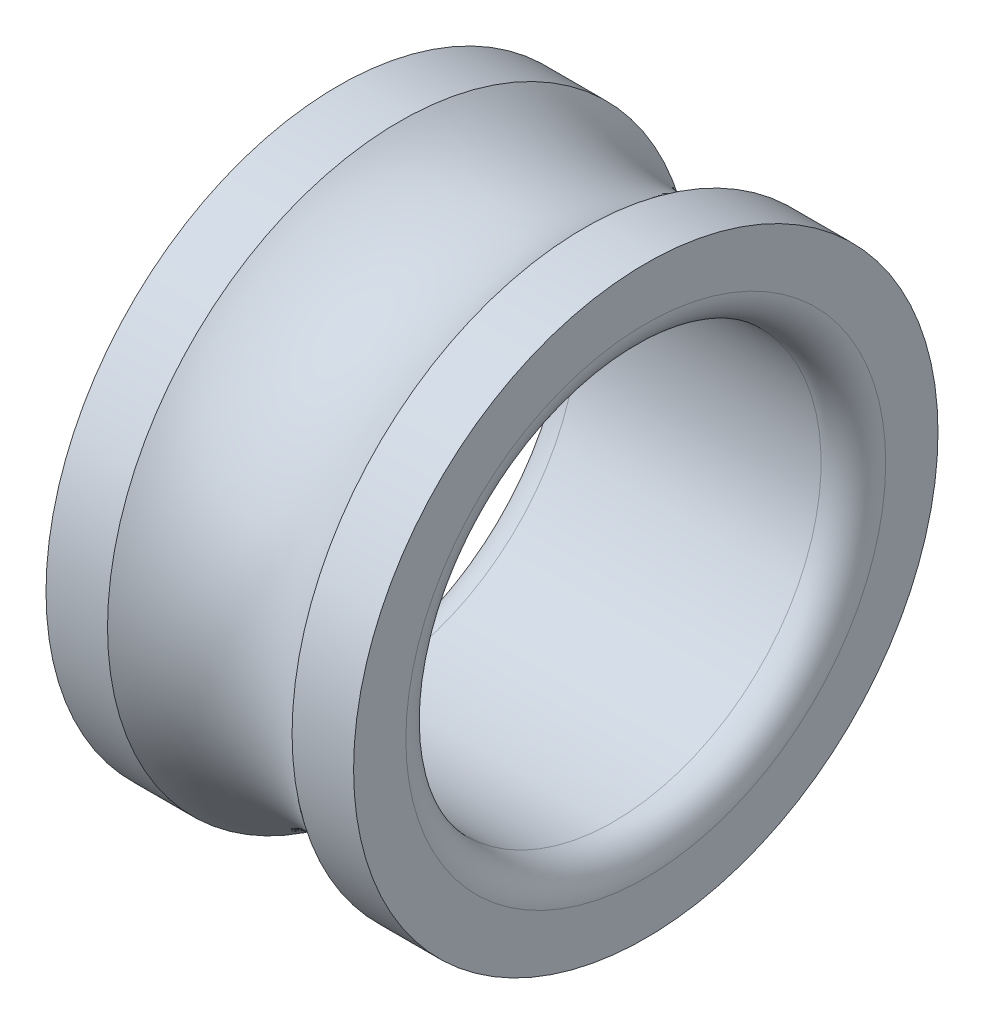
SolidWorks part; units mm, degrees
ref_plane "Front Plane" through (0, 0, 0) normal (0, 0, 1) x (1, 0, 0)
ref_plane "Top Plane" through (0, 0, 0) normal (0, 1, 0) x (1, 0, 0)
ref_plane "Right Plane" through (0, 0, 0) normal (1, 0, 0) x (0, 0, -1)
sketch "Sketch1" plane through (0, 0, 0) normal (0, 0, 1) x (1, 0, 0)
  line L0 (-10, 0) -> (13.4848, 0) construction
  line L1 (0, 13.5) -> (0, 0) construction
  line L2 (10, 19) -> (6, 19)
  line L3 (10, 19) -> (10, 15.6)
  line L4 (7.9, 13.5) -> (-7.9, 13.5)
  line L5 (-10, 19) -> (-10, 15.6)
  line L6 (10, 19) -> (-10, 13.5) construction
  line L7 (10, 13.5) -> (-10, 19) construction
  line L8 (-6, 19) -> (-10, 19)
  arc A0 (6, 19) -> (-6, 19) centre (0, 27) cw
  arc A1 (10, 15.6) -> (7.9, 13.5) centre (7.9, 15.6) cw
  arc A2 (-7.9, 13.5) -> (-10, 15.6) centre (-7.9, 15.6) cw
  point P3 (0, 16.25)
  dimension "D5" = 10
  dimension "D6" = 2.1
  dimension "D1" = 20
  dimension "D2" = 13.5
  dimension "D3" = 19
  dimension "D4" = 8
revolve "Revolve1" add sketch "Sketch1" angle 360 about L0
